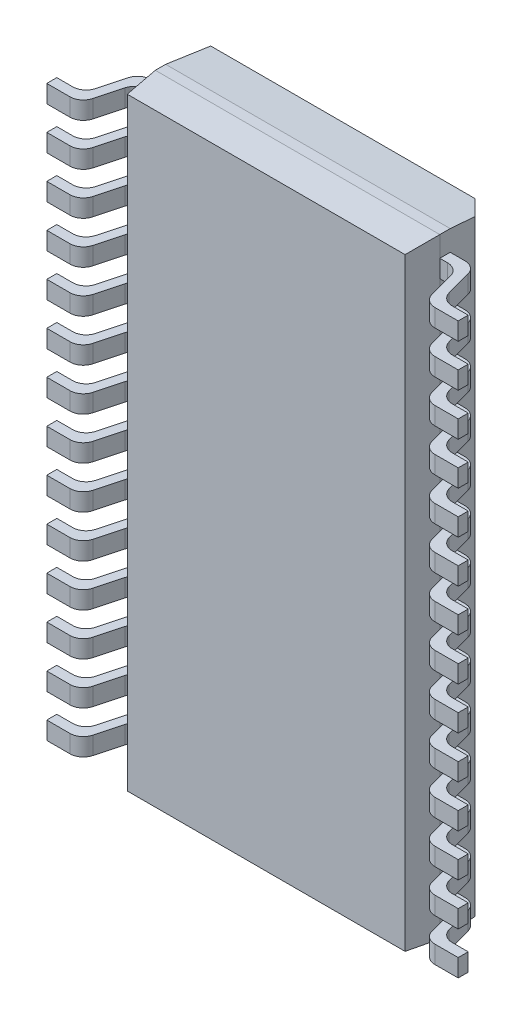
SolidWorks part; units mm, degrees
ref_plane "Front Plane" through (0, 0, 0) normal (0, 0, 1) x (1, 0, 0)
ref_plane "Top Plane" through (0, 0, 0) normal (0, 1, 0) x (1, 0, 0)
ref_plane "Right Plane" through (0, 0, 0) normal (1, 0, 0) x (0, 0, -1)
sketch "Sketch1" plane through (0, 0, 0) normal (0, 1, 0) x (1, 0, 0)
  line L0 (-0.421, 0.1119) -> (-0.6238, -0.6452)
  line L1 (-1.7047, -0.6417) -> (-1.2261, -0.6417)
  line L2 (-1.7047, -0.6417) -> (-1.7047, -0.9417)
  line L3 (-1.7047, -0.9417) -> (-1.0102, -0.9417)
  line L5 (-0.2478, 0.7183) -> (0.1953, 0.7183)
  line L7 (-0.0346, 0.4083) -> (0.1953, 0.4083)
  line L8 (0.1953, 0.7183) -> (0.1953, 0.4083)
  line L9 (-0.6342, 0.4219) -> (-0.8397, -0.3452)
  arc A0 (-0.2478, 0.7183) -> (-0.6342, 0.4219) centre (-0.2478, 0.3183) ccw
  arc A1 (-0.421, 0.1119) -> (-0.0346, 0.4083) centre (-0.0346, 0.0083) cw
  arc A2 (-1.0102, -0.9417) -> (-0.6238, -0.6452) centre (-1.0102, -0.5417) ccw
  arc A3 (-1.2261, -0.6417) -> (-0.8397, -0.3452) centre (-1.2261, -0.2417) ccw
  point P6 (-0.5547, 0.7183)
  dimension "D3" = 0.4
  dimension "D1" = 0.75
  dimension "D2" = 0.3
  dimension "D4" = 0.31
  dimension "D5" = 1.9
  dimension "D6" = 1.66
  dimension "D7" = 75
  dimension "D8" = 75
extrude "Boss-Extrude1" add sketch "Sketch1" along normal blind 0.53 contours L5 L8 L7 A1 L0 A2 L3 L2 L1 A3 L9 A0
pattern_linear "LPattern1" count 14 spacing 1.27 along (0, 1, 0) of bodies 101
ref_plane "Plane1" through (4.4553, 0, 0) normal (1, 0, 0) x (0, 0, -1)
mirror "Mirror1" about plane through (4.4553, 0, 0) normal (1, 0, 0) of bodies 101 102 103 104 105 106 107 108 109 110 111 112 113 114
sketch "Sketch3" plane through (0, 0, -0.7183) normal (0, 0, -1) x (-1, 0, 0)
  line L0 (-9.1583, 17.04) -> (-8.7153, 17.04) construction
  line L1 (-8.7153, 17.655) -> (-0.1953, 17.655)
  line L2 (-8.7153, 17.655) -> (-8.7153, -0.615)
  line L3 (-8.7153, -0.615) -> (-0.1953, -0.615)
  line L4 (-0.1953, 17.655) -> (-0.1953, -0.615)
  line L5 (-0.1953, 17.04) -> (-0.1953, 16.51) construction
  dimension "D1" = 8.52
  dimension "D2" = 18.27
  dimension "D3" = 0.615
  dimension "D4" = 0
extrude "Boss-Extrude2" add sketch "Sketch3" against normal blind 1.25 contours L3 L4 L1 L2
sketch "Sketch6" plane through (0, 0, -0.7183) normal (0, 0, -1) x (-1, 0, 0)
  line L1 (-8.7153, -0.615) -> (-0.1953, -0.615)
  line L2 (-8.7153, -0.615) -> (-8.7153, 17.655)
  line L3 (-8.7153, 17.655) -> (-0.1953, 17.655)
  line L4 (-0.1953, -0.615) -> (-0.1953, 17.655)
extrude "Boss-Extrude3" add sketch "Sketch6" along normal blind 1.25
chamfer "Chamfer1" distance 0.5 angle 45 1 edges at (8.7153, 8.52, -1.9683)
sketch "Sketch7" plane through (0, 0, -1.9683) normal (0, 0, -1) x (-1, 0, 0)
  line L0 (-0.1953, 17.655) -> (-8.2153, 17.655) construction
  line L1 (-8.2153, 17.655) -> (-8.2153, -0.615) construction
  circle A0 centre (-7.4153, 16.855) radius 0.6
  dimension "D1" = 1.2
  dimension "D2" = 0.8
  dimension "D3" = 0.8
extrude "Cut-Extrude1" cut sketch "Sketch7" against normal blind 0.2
sketch "Sketch8" plane through (0, -0.615, 0) normal (0, -1, 0) x (1, 0, 0)
  line L0 (0.2953, 0.5317) -> (0.1953, -0.4083)
  line L1 (8.7153, 0.5317) -> (0.1953, 0.5317) construction
  line L2 (0.1953, -0.4083) -> (0.1953, 0.5317)
  line L3 (0.1953, 0.5317) -> (0.2953, 0.5317)
  line L4 (0.1953, -0.7183) -> (0.1953, -1.9683)
  line L5 (0.1953, -1.9683) -> (0.2953, -1.9683)
  line L6 (8.2153, -1.9683) -> (0.1953, -1.9683) construction
  line L7 (0.2953, -1.9683) -> (0.1953, -0.7183)
  line L8 (8.7153, -0.4083) -> (8.7153, 0.5317)
  line L9 (8.7153, 0.5317) -> (8.6153, 0.5317)
  line L10 (8.6153, 0.5317) -> (8.7153, -0.4083)
  dimension "D1" = 0.1
  dimension "D2" = 0.1
  dimension "D3" = 0.1
extrude "Cut-Extrude2" cut sketch "Sketch8" against normal through all
sketch "Sketch9" plane through (0.1953, 0, 0) normal (-1, 0, 0) x (0, 0, 1)
  line L0 (-0.7183, -0.615) -> (-1.9683, -0.515)
  line L1 (-1.9683, 17.655) -> (-1.9683, -0.615) construction
  line L2 (-1.9683, -0.515) -> (-1.9683, -0.615)
  line L3 (-1.9683, -0.615) -> (-0.7183, -0.615)
  line L4 (-0.4083, -0.615) -> (0.5317, -0.615)
  line L5 (0.5317, -0.615) -> (0.5317, -0.515)
  line L6 (0.5317, 17.655) -> (0.5317, -0.615) construction
  line L7 (0.5317, -0.515) -> (-0.4083, -0.615)
  line L8 (-0.7183, 17.655) -> (-1.9683, 17.655)
  line L9 (-1.9683, 17.655) -> (-1.9683, 17.555)
  line L10 (-1.9683, 17.555) -> (-0.7183, 17.655)
  line L11 (-0.4083, 17.655) -> (0.5317, 17.655)
  line L12 (0.5317, 17.655) -> (0.5317, 17.555)
  line L13 (0.5317, 17.555) -> (-0.4083, 17.655)
  dimension "D1" = 0.1
  dimension "D2" = 0.1
  dimension "D3" = 0.1
  dimension "D4" = 0.1
extrude "Cut-Extrude3" cut sketch "Sketch9" against normal through all
